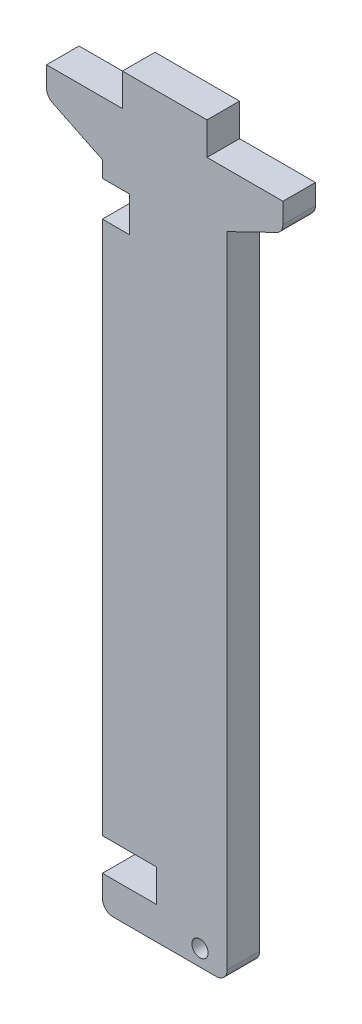
SolidWorks part; units mm, degrees
ref_plane "Plan de face" through (0, 0, 0) normal (0, 0, 1) x (1, 0, 0)
ref_plane "Plan de dessus" through (0, 0, 0) normal (0, 1, 0) x (1, 0, 0)
ref_plane "Plan de droite" through (0, 0, 0) normal (1, 0, 0) x (0, 0, -1)
sketch "Esquisse1" plane through (0, 0, 0) normal (0, 0, 1) x (1, 0, 0)
  line L1 (0, 0) -> (43.6, 0)
  line L2 (0, 0) -> (0, 130)
  line L3 (0, 130) -> (43.6, 130)
  line L4 (43.6, 0) -> (43.6, 130)
  dimension "D1" = 43.6
  dimension "D2" = 130
extrude "Boss.-Extru.1" add sketch "Esquisse1" along normal blind 6
sketch "Esquisse2" plane through (0, 0, 6) normal (0, 0, 1) x (1, 0, 0)
  line L1 (43.6, 0) -> (33.3, 0)
  line L3 (10.3, 120) -> (0, 125)
  line L4 (33.3, 0) -> (33.3, 120)
  line L5 (0, 0) -> (10.3, 0)
  line L6 (0, 130) -> (0, 0) construction
  line L7 (0, 125) -> (0, 0)
  line L8 (10.3, 0) -> (10.3, 120)
  line L10 (43.6, 0) -> (43.6, 125)
  line L11 (43.6, 0) -> (43.6, 130) construction
  line L13 (43.6, 125) -> (33.3, 120)
  line L14 (43.6, 130) -> (0, 130) construction
  dimension "D1" = 120
  dimension "D2" = 120
  dimension "D3" = 10
  dimension "D4" = 125
  dimension "D5" = 5
  dimension "D6" = 10.3
  dimension "D7" = 5
  dimension "D8" = 10.3
extrude "Enlèv. mat.-Extru.1" cut sketch "Esquisse2" against normal blind 6
sketch "Esquisse4" plane through (0, 0, 6) normal (0, 0, 1) x (1, 0, 0)
  line L0 (43.6, 130) -> (0, 130) construction
  line L1 (14, 130) -> (29.6, 130)
  line L2 (14, 130) -> (14, 136)
  line L3 (14, 136) -> (29.6, 136)
  line L4 (29.6, 130) -> (29.6, 136)
  line L5 (43.6, 125) -> (43.6, 130) construction
  line L6 (0, 130) -> (0, 125) construction
  dimension "D1" = 6
  dimension "D2" = 15.6
  dimension "D3" = 14
  dimension "D4" = 14
extrude "Boss.-Extru.2" add sketch "Esquisse4" against normal blind 6
sketch "Esquisse6" plane through (0, 0, 6) normal (0, 0, 1) x (1, 0, 0)
  line L0 (10.3, 0) -> (10.3, 120) construction
  line L1 (10.3, 6) -> (20.3, 6)
  line L2 (10.3, 6) -> (10.3, 12)
  line L3 (10.3, 12) -> (20.3, 12)
  line L4 (20.3, 6) -> (20.3, 12)
  line L6 (10.3, 0) -> (33.3, 0) construction
  line L7 (10.3, 0) -> (10.3, 120) construction
  line L8 (10.3, 117) -> (15.3, 117)
  line L9 (10.3, 117) -> (10.3, 110.5)
  line L10 (10.3, 110.5) -> (15.3, 110.5)
  line L11 (15.3, 117) -> (15.3, 110.5)
  dimension "D1" = 6
  dimension "D2" = 10
  dimension "D3" = 6
  dimension "D4" = 6.5
  dimension "D5" = 5
  dimension "D6" = 3
extrude "Enlèv. mat.-Extru.3" cut sketch "Esquisse6" against normal blind 6
fillet "Congé8" radius 2 2 edges at (33.3, 0, 3) (10.3, 0, 3)
fillet "Congé9" radius 2 2 edges at (43.6, 125, 3) (0, 125, 3)
sketch "Esquisse7" plane through (0, 0, 6) normal (0, 0, 1) x (1, 0, 0)
  line L0 (33.3, 120) -> (33.3, 2) construction
  line L1 (12.3, 0) -> (31.3, 0) construction
  circle A0 centre (28.3, 3) radius 1.5
  dimension "D1" = 3
  dimension "D2" = 5
  dimension "D3" = 3
extrude "Enlèv. mat.-Extru.4" cut sketch "Esquisse7" against normal blind 6
